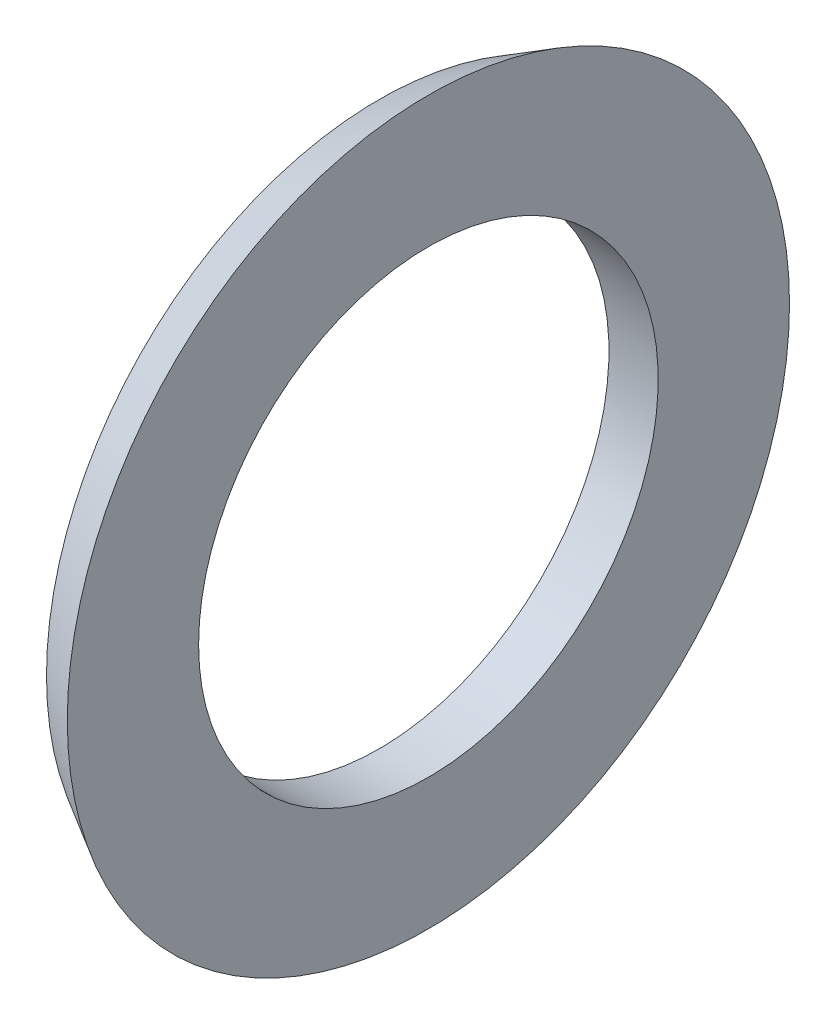
SolidWorks part; units mm, degrees
ref_plane "Plan1" through (0, 0, 0) normal (0, 0, 1) x (1, 0, 0)
ref_plane "Plan2" through (0, 0, 0) normal (0, 1, 0) x (1, 0, 0)
ref_plane "Plan3" through (0, 0, 0) normal (1, 0, 0) x (0, 0, -1)
sketch "Esquisse1" plane through (0, 0, 0) normal (0, 0, 1) x (1, 0, 0)
  line L0 (0, 14) -> (0, 20.2679)
  line L1 (0, 20.2679) -> (3, 22)
  line L2 (3, 22) -> (3, 14)
  line L3 (3, 14) -> (0, 14)
  line L4 (-20, 0) -> (30, 0) construction
  dimension "D1" = 30
  dimension "D2" = 14
  dimension "D3" = 22
  dimension "D4" = 3
revolve "Base-Révolution" add sketch "Esquisse1" angle 360 about L4
